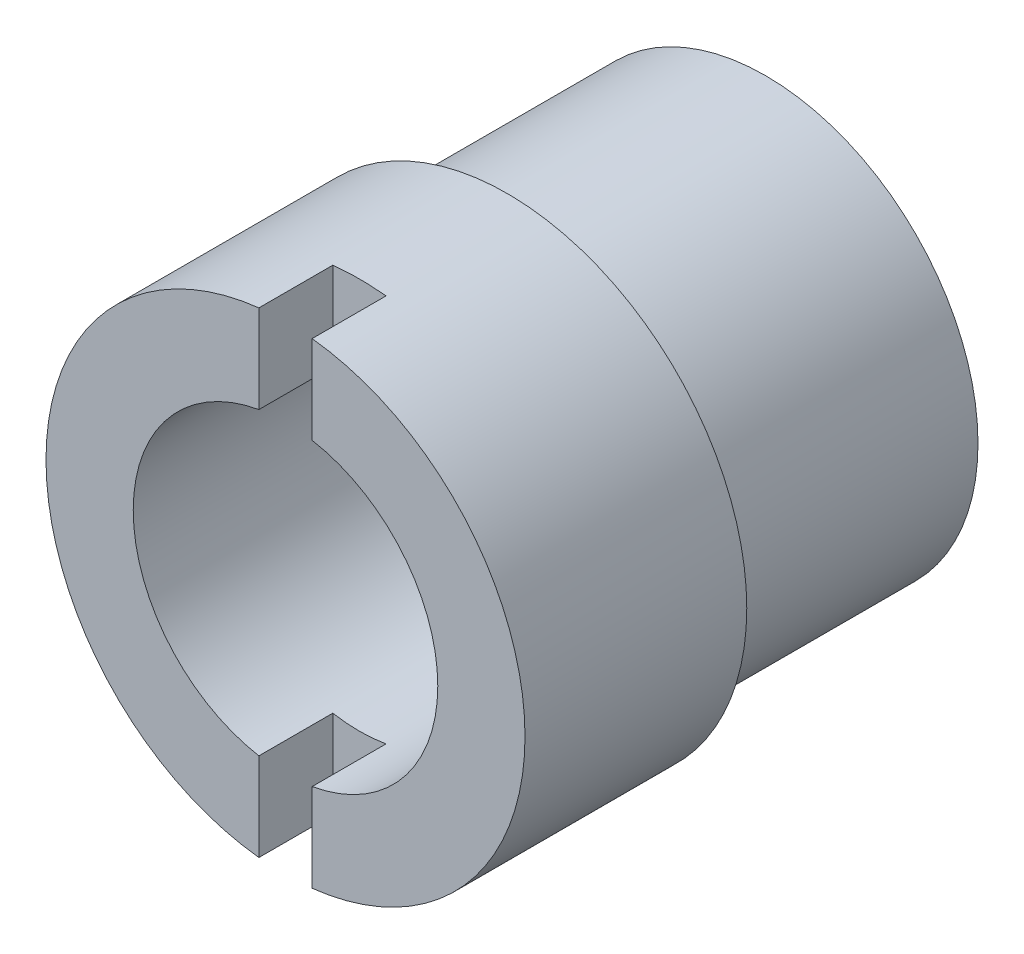
SolidWorks part; units mm, degrees
ref_plane "Front Plane" through (0, 0, 0) normal (0, 0, 1) x (1, 0, 0)
ref_plane "Top Plane" through (0, 0, 0) normal (0, 1, 0) x (1, 0, 0)
ref_plane "Right Plane" through (0, 0, 0) normal (1, 0, 0) x (0, 0, -1)
sketch "Sketch1" plane through (0, 0, 0) normal (0, 0, 1) x (1, 0, 0)
  circle A0 centre (0, 0) radius 10.287
  circle A1 centre (0, 0) radius 6.5405
  dimension "D1" = 13.081
  dimension "D2" = 20.574
extrude "Boss-Extrude1" add sketch "Sketch1" against normal blind 9.525
cosmetic thread "Cosmetic Thread1" parameters "D1"=9.525, "D2"=19.3802
sketch "Sketch3" plane through (0, 0, -9.525) normal (0, 0, -1) x (-1, 0, 0)
  circle A0 centre (0, 0) radius 9.1186
  circle A2 centre (0, 0) radius 6.5405
  dimension "D1" = 18.2372
extrude "Boss-Extrude3" add sketch "Sketch3" along normal blind 11.0998
sketch "Sketch4" plane through (0, 0, 0) normal (0, 1, 0) x (1, 0, 0)
  line L0 (-10.287, 0) -> (10.287, 0) construction
  line L1 (-1.143, 0) -> (1.143, 0)
  line L2 (-1.143, 0) -> (-1.143, 3.175)
  line L3 (-1.143, 3.175) -> (1.143, 3.175)
  line L4 (1.143, 0) -> (1.143, 3.175)
  dimension "D1" = 2.286
  dimension "D2" = 3.175
extrude "Cut-Extrude1" cut sketch "Sketch4" against normal mid plane 28.8798
